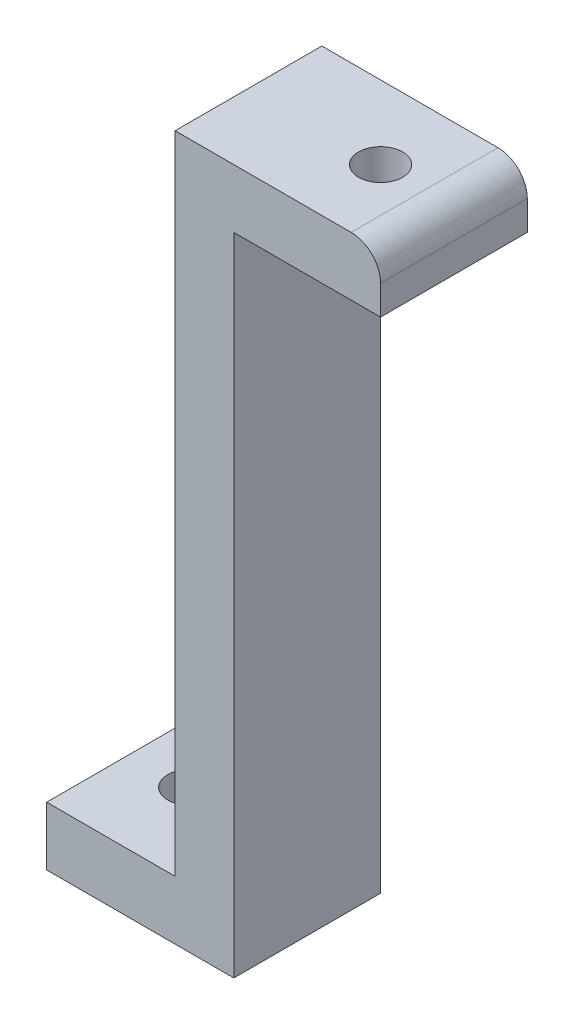
SolidWorks part; units mm, degrees
ref_plane "Front Plane" through (0, 0, 0) normal (0, 0, 1) x (1, 0, 0)
ref_plane "Top Plane" through (0, 0, 0) normal (0, 1, 0) x (1, 0, 0)
ref_plane "Right Plane" through (0, 0, 0) normal (1, 0, 0) x (0, 0, -1)
sketch "Sketch1" plane through (0, 0, 0) normal (0, 0, 1) x (1, 0, 0)
  line L0 (0, 0) -> (-14, 0)
  line L1 (-14, 0) -> (-14, -44)
  line L2 (-14, -44) -> (-22.75, -44)
  line L3 (-22.75, -44) -> (-22.75, -48)
  line L4 (-22.75, -48) -> (-10, -48)
  line L5 (-10, -48) -> (-10, -4)
  line L6 (-10, -4) -> (0, -4)
  line L7 (0, -4) -> (0, 0)
  dimension "D1" = 4
  dimension "D2" = 4
  dimension "D3" = 4
  dimension "D4" = 44
  dimension "D5" = 12.75
  dimension "D6" = 10
extrude "Boss-Extrude1" add sketch "Sketch1" along normal blind 10
sketch "Sketch2" plane through (0, -44, 0) normal (0, 1, 0) x (1, 0, 0)
  line L0 (-22.75, -10) -> (-22.75, 0) construction
  circle A0 centre (-18.75, -4.25) radius 1.5
  point P4 (-22.75, -5)
  dimension "D1" = 3
  dimension "D2" = 4
  dimension "D3" = 0.75
extrude "Cut-Extrude1" cut sketch "Sketch2" against normal blind 10
sketch "Sketch3" plane through (0, -4, 0) normal (0, -1, 0) x (-1, 0, 0)
  line L0 (0, -10) -> (0, 0) construction
  line L2 (10, -10) -> (10, 0) construction
  circle A0 centre (5, -5) radius 1.5
  point P4 (0, -5)
  dimension "D1" = 3
  dimension "D2" = 0
  dimension "D3" = 5
extrude "Cut-Extrude2" cut sketch "Sketch3" against normal blind 10
fillet "Fillet1" radius 2 1 edges at (0, 0, 5)
